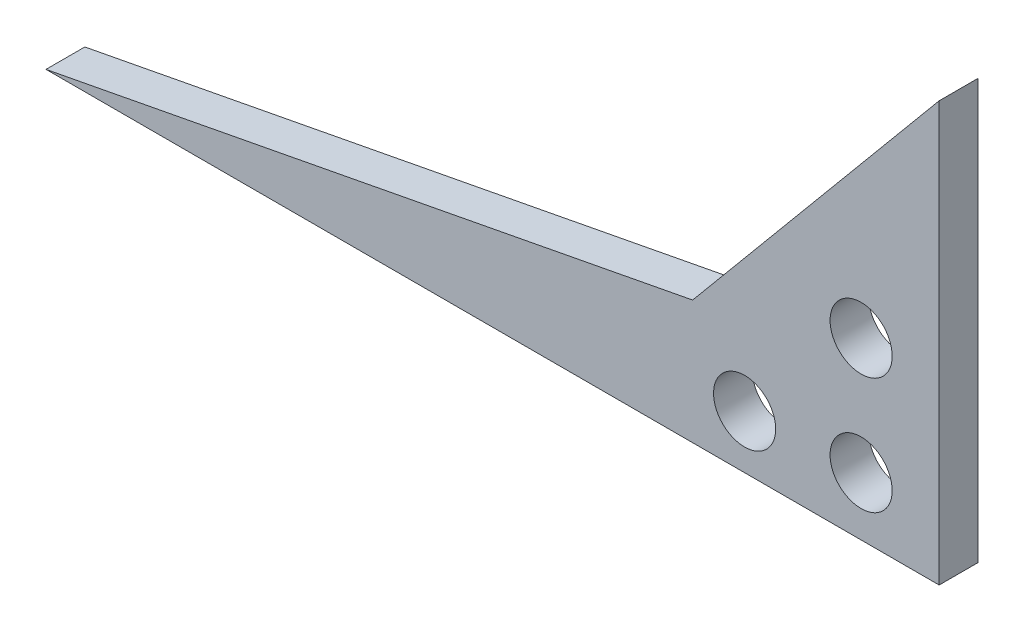
SolidWorks part; units mm, degrees
material "Malleable Cast Iron"
ref_plane "Front Plane" through (0, 0, 0) normal (0, 0, 1) x (1, 0, 0)
ref_plane "Top Plane" through (0, 0, 0) normal (0, 1, 0) x (1, 0, 0)
ref_plane "Right Plane" through (0, 0, 0) normal (1, 0, 0) x (0, 0, -1)
sketch "Sketch1" plane through (0, 0, 0) normal (0, 0, 1) x (1, 0, 0)
  line L0 (-27.3694, 43.0299) -> (-27.3694, -10.9701)
  line L1 (-72.3694, -10.9701) -> (-27.3694, -10.9701)
  line L2 (-27.3694, 43.0299) -> (-72.3694, -10.9701) construction
  line L3 (-72.3694, -10.9701) -> (-142.3694, -10.9701)
  line L4 (-142.3694, -10.9701) -> (-59.1123, 4.9384)
  line L5 (-59.1123, 4.9384) -> (-27.3694, 43.0299)
  dimension "D1" = 50.194
  dimension "D2" = 45
  dimension "D3" = 70
extrude "Boss-Extrude1" add sketch "Sketch1" along normal blind 5
sketch "Sketch2" plane through (0, 0, 5) normal (0, 0, 1) x (1, 0, 0)
  line L0 (-142.3694, -10.9701) -> (-27.3694, -10.9701) construction
  circle A0 centre (-37.4194, -3.4701) radius 4
  circle A1 centre (-37.4194, 11.5299) radius 4
  circle A2 centre (-52.4194, -4.1057) radius 4
  dimension "D1" = 7.5
  dimension "D2" = 15
  dimension "D3" = 15
extrude "Cut-Extrude1" cut sketch "Sketch2" against normal up to surface (5 mm away) up to face at (-64.0551, 6.507, 0)
